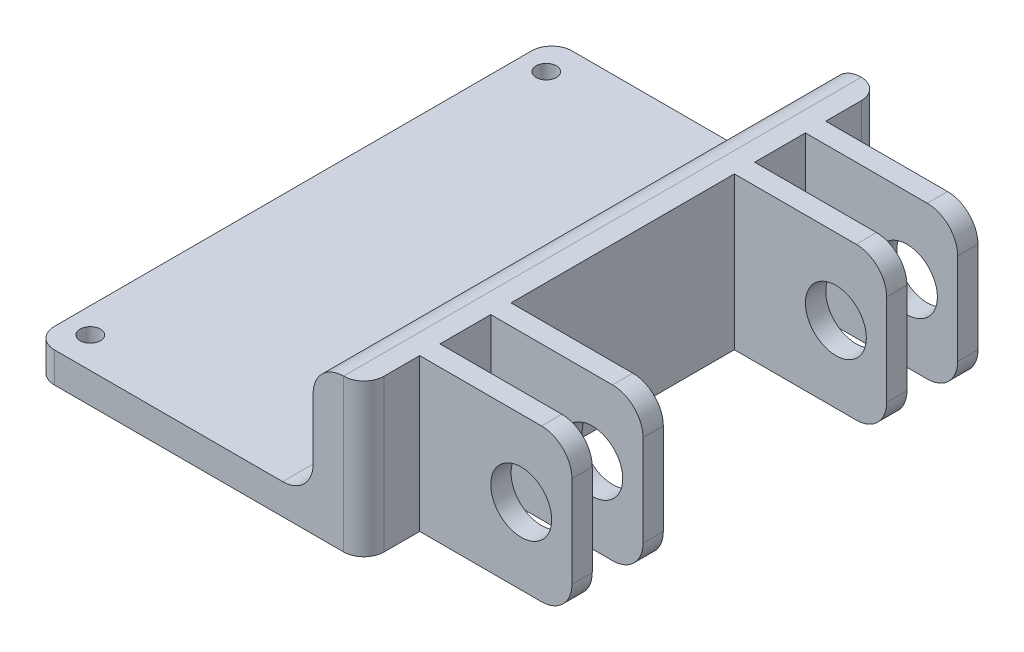
SolidWorks part; units mm, degrees
ref_plane "Front Plane" through (0, 0, 0) normal (0, 0, 1) x (1, 0, 0)
ref_plane "Top Plane" through (0, 0, 0) normal (0, 1, 0) x (1, 0, 0)
ref_plane "Right Plane" through (0, 0, 0) normal (1, 0, 0) x (0, 0, -1)
sketch "Sketch1" plane through (0, 0, 0) normal (0, 1, 0) x (1, 0, 0)
  line L0 (-36.1494, 0) -> (46.1149, 0) construction
  line L1 (-30, 25.5) -> (30, 25.5)
  line L2 (-30, 25.5) -> (-30, -25.5)
  line L3 (-30, -25.5) -> (30, -25.5)
  line L4 (30, 25.5) -> (30, 18)
  line L5 (-30, 25.5) -> (30, -25.5) construction
  line L6 (-30, -25.5) -> (30, 25.5) construction
  line L7 (0, 30.6782) -> (0, -36.3448) construction
  line L8 (30, -13) -> (15, -13)
  line L9 (30, 18) -> (15, 18)
  line L11 (30, 13) -> (15, 13)
  line L12 (15, 18) -> (15, 13)
  line L13 (15, -18) -> (15, -13)
  line L14 (30, -18) -> (15, -18)
  line L16 (30, 13) -> (30, -13)
  line L17 (30, -18) -> (30, -25.5)
  point P0 (0, 0)
  dimension "D1" = 51
  dimension "D2" = 60
  dimension "D3" = 5
  dimension "D4" = 15
  dimension "D5" = 13
extrude "Boss-Extrude1" add sketch "Sketch1" along normal blind 15
sketch "Sketch2" plane through (0, 0, 25.5) normal (0, 0, 1) x (1, 0, 0)
  line L0 (-30, 15) -> (30, 15) construction
  line L1 (-30, 0) -> (30, 0) construction
  line L2 (30, 15) -> (30, 0) construction
  circle A0 centre (25, 7.5) radius 3
  dimension "D1" = 7.5
  dimension "D2" = 7.5
  dimension "D3" = 5
  dimension "D4" = 6
extrude "Cut-Extrude1" cut sketch "Sketch2" against normal blind 51
fillet "Fillet1" radius 3 1 edges at (30, 15, 21.75)
fillet "Fillet2" radius 3 1 edges at (30, 15, 0)
fillet "Fillet3" radius 3 1 edges at (30, 15, -21.75)
fillet "Fillet4" radius 3 1 edges at (30, 0, 21.75)
fillet "Fillet5" radius 3 1 edges at (30, 0, 0)
fillet "Fillet6" radius 3 1 edges at (30, 0, -21.75)
sketch "Sketch4" plane through (0, 15, 0) normal (0, 1, 0) x (1, 0, 0)
  line L0 (-30, 25.5) -> (-30, -25.5)
  line L1 (-30, 25.5) -> (10, 25.5)
  line L2 (-30, -25.5) -> (10, -25.5)
  line L3 (10, 25.5) -> (10, -25.5)
  dimension "D1" = 40
extrude "Cut-Extrude2" cut sketch "Sketch4" against normal blind 12
sketch "Sketch5" plane through (0, 3, 0) normal (0, 1, 0) x (1, 0, 0)
  line L0 (-30, -25.5) -> (10, -25.5) construction
  line L1 (10, -25.5) -> (10, 25.5) construction
  line L4 (10, 25.5) -> (-30, 25.5) construction
  line L5 (10, -25.5) -> (10, 25.5) construction
  circle A2 centre (-14.99, 22.46) radius 1
  circle A3 centre (-14.99, -22.46) radius 1
  dimension "D2" = 24.99
  dimension "D3" = 24.99
  dimension "D10" = 2
  dimension "D11" = 2
  dimension "D12" = 3.04
  dimension "D13" = 3.04
extrude "Cut-Extrude3" cut sketch "Sketch5" against normal blind 12
fillet "Fillet7" radius 3 1 edges at (10, 15, 0)
fillet "Fillet8" radius 3 1 edges at (10, 3, 0)
sketch "Sketch7" plane through (0, 15, 0) normal (0, 1, 0) x (1, 0, 0)
  line L0 (30, 13) -> (30, -13) construction
  line L1 (30, 11) -> (15, 11)
  line L2 (30, 11) -> (30, -11)
  line L3 (30, -11) -> (15, -11)
  line L4 (15, 11) -> (15, -11)
  line L5 (27, 13) -> (15, 13) construction
  line L6 (15, -13) -> (27, -13) construction
  dimension "D1" = 15
  dimension "D2" = 2
  dimension "D3" = 2
extrude "Cut-Extrude5" cut sketch "Sketch7" against normal blind 20
sketch "Sketch9" plane through (0, 15, 0) normal (0, 1, 0) x (1, 0, 0)
  line L1 (30, 25.5) -> (15, 25.5)
  line L2 (30, 25.5) -> (30, 20)
  line L3 (30, 20) -> (15, 20)
  line L4 (15, 25.5) -> (15, 20)
  line L5 (30, -25.5) -> (15, -25.5)
  line L6 (30, -25.5) -> (30, -20)
  line L7 (30, -20) -> (15, -20)
  line L8 (15, -25.5) -> (15, -20)
  dimension "D1" = 15
  dimension "D2" = 5.5
  dimension "D3" = 5.5
  dimension "D4" = 15
extrude "Cut-Extrude6" cut sketch "Sketch9" against normal blind 20
fillet "Fillet11" radius 2 2 edges at (14, 15, 25.5) (15, 7.5, 25.5)
fillet "Fillet12" radius 2 2 edges at (14, 15, -25.5) (15, 7.5, -25.5)
sketch "Sketch11" plane through (0, 3, 0) normal (0, 1, 0) x (1, 0, 0)
  line L0 (7, 25.5) -> (-30, 25.5) construction
  line L1 (-17.49, 25.5) -> (-30, 25.5)
  line L2 (-17.49, 25.5) -> (-17.49, -25.5)
  line L3 (-17.49, -25.5) -> (-30, -25.5)
  line L4 (-30, 25.5) -> (-30, -25.5)
  circle A0 centre (-14.99, 22.46) radius 1 construction
  dimension "D1" = 2.5
extrude "Cut-Extrude7" cut sketch "Sketch11" against normal blind 3
fillet "Fillet13" radius 2 1 edges at (-17.49, 1.5, 25.5)
fillet "Fillet14" radius 2 1 edges at (-17.49, 1.5, -25.5)
